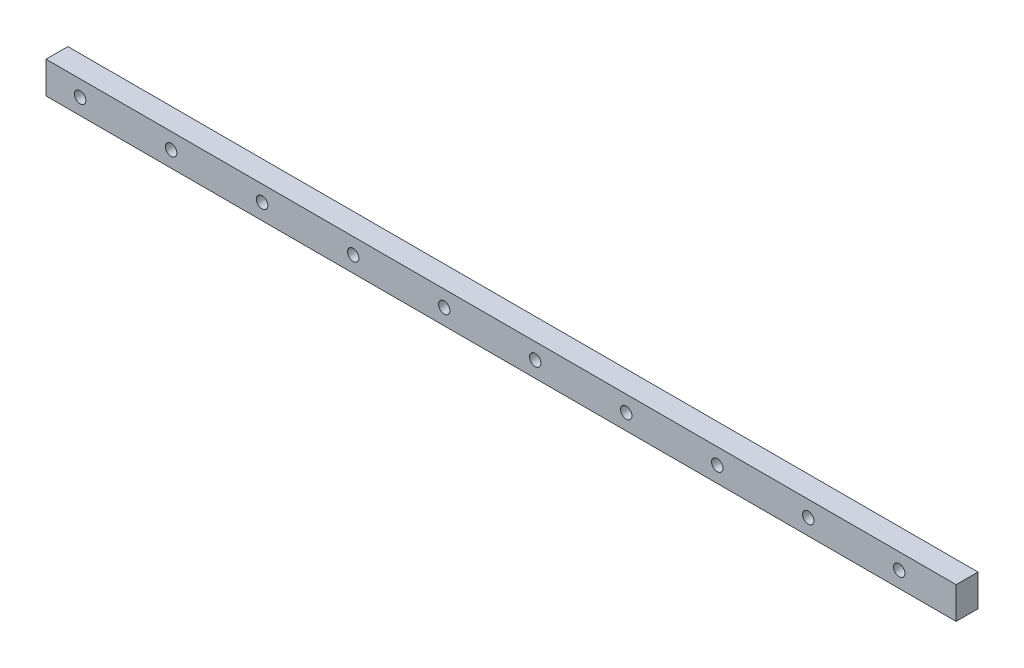
SolidWorks part; units mm, degrees
ref_plane "前视基准面" through (0, 0, 0) normal (0, 0, 1) x (1, 0, 0)
ref_plane "上视基准面" through (0, 0, 0) normal (0, 1, 0) x (1, 0, 0)
ref_plane "右视基准面" through (0, 0, 0) normal (1, 0, 0) x (0, 0, -1)
other "Configuration Table"
sketch "草图1" plane through (0, 0, 0) normal (0, 0, 1) x (1, 0, 0)
  line L1 (0, 0) -> (200, 0)
  line L2 (0, 0) -> (0, -7)
  line L3 (0, -7) -> (200, -7)
  line L4 (200, 0) -> (200, -7)
  circle A0 centre (7.5, -3.5) radius 1.25
  circle A1 centre (27.5, -3.5) radius 1.25
  circle A2 centre (47.5, -3.5) radius 1.25
  circle A3 centre (67.5, -3.5) radius 1.25
  circle A4 centre (87.5, -3.5) radius 1.25
  circle A5 centre (107.5, -3.5) radius 1.25
  circle A6 centre (127.5, -3.5) radius 1.25
  circle A7 centre (147.5, -3.5) radius 1.25
  circle A8 centre (167.5, -3.5) radius 1.25
  circle A9 centre (187.5, -3.5) radius 1.25
  dimension "D3" = 2.5
  dimension "D4" = 7.5
  dimension "D1" = 200
  dimension "D2" = 7
  dimension "D5" = 10
extrude "凸台-拉伸1" add sketch "草图1" along normal blind 4.8
